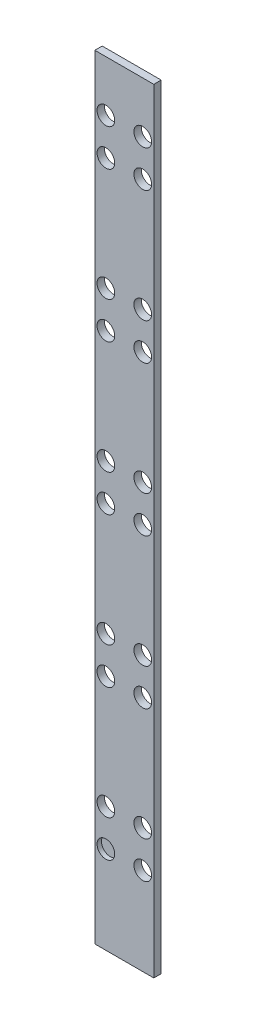
SolidWorks part; units mm, degrees
ref_plane "Front Plane" through (0, 0, 0) normal (0, 0, 1) x (1, 0, 0)
ref_plane "Top Plane" through (0, 0, 0) normal (0, 1, 0) x (1, 0, 0)
ref_plane "Right Plane" through (0, 0, 0) normal (1, 0, 0) x (0, 0, -1)
sketch "Sketch3" plane through (0, 0, 0) normal (0, 1, 0) x (1, 0, 0)
  line L0 (-2, 0.35) -> (-2, -0.15)
  line L1 (-2, -0.15) -> (2, -0.15)
  line L2 (2, -0.15) -> (2, 0.35)
  line L3 (2, 0.35) -> (-2, 0.35)
extrude "Boss-Extrude1" add sketch "Sketch3" against normal blind 52.5
sketch "Sketch4" plane through (0, 0, 0.15) normal (0, 0, 1) x (1, 0, 0)
  circle A0 centre (1.25, -3.45) radius 0.6
extrude "Cut-Extrude1" cut sketch "Sketch4" against normal blind 0.5
sketch "Sketch5" plane through (0, 0, 0.15) normal (0, 0, 1) x (1, 0, 0)
  circle A0 centre (1.25, -5.95) radius 0.6
  circle A2 centre (1.25, -3.45) radius 0.6 construction
  dimension "D1" = 2.5
extrude "Cut-Extrude2" cut sketch "Sketch5" against normal blind 0.5
sketch "Sketch6" plane through (0, 0, 0.15) normal (0, 0, 1) x (1, 0, 0)
  circle A0 centre (1.25, -13.6) radius 0.6
extrude "Cut-Extrude3" cut sketch "Sketch6" against normal blind 0.5
sketch "Sketch7" plane through (0, 0, 0.15) normal (0, 0, 1) x (1, 0, 0)
  circle A0 centre (1.25, -16.1) radius 0.6
extrude "Cut-Extrude4" cut sketch "Sketch7" against normal blind 0.5
sketch "Sketch8" plane through (0, 0, 0.15) normal (0, 0, 1) x (1, 0, 0)
  circle A0 centre (1.25, -23.75) radius 0.6
extrude "Cut-Extrude5" cut sketch "Sketch8" against normal blind 0.5
sketch "Sketch9" plane through (0, 0, 0.15) normal (0, 0, 1) x (1, 0, 0)
  circle A0 centre (1.25, -26.25) radius 0.6
extrude "Cut-Extrude6" cut sketch "Sketch9" against normal blind 0.5
sketch "Sketch10" plane through (0, 0, 0.15) normal (0, 0, 1) x (1, 0, 0)
  circle A0 centre (1.25, -33.9) radius 0.6
extrude "Cut-Extrude7" cut sketch "Sketch10" against normal blind 0.5
sketch "Sketch11" plane through (0, 0, 0.15) normal (0, 0, 1) x (1, 0, 0)
  circle A0 centre (1.25, -36.4) radius 0.6
extrude "Cut-Extrude8" cut sketch "Sketch11" against normal blind 0.5
sketch "Sketch12" plane through (0, 0, 0.15) normal (0, 0, 1) x (1, 0, 0)
  circle A0 centre (1.25, -44.05) radius 0.6
extrude "Cut-Extrude9" cut sketch "Sketch12" against normal blind 0.5
sketch "Sketch13" plane through (0, 0, 0.15) normal (0, 0, 1) x (1, 0, 0)
  circle A0 centre (1.25, -46.55) radius 0.6
extrude "Cut-Extrude10" cut sketch "Sketch13" against normal blind 0.5
sketch "Sketch14" plane through (0, 0, 0.15) normal (0, 0, 1) x (1, 0, 0)
  circle A0 centre (-1.25, -3.45) radius 0.6
extrude "Cut-Extrude11" cut sketch "Sketch14" against normal blind 0.5
sketch "Sketch15" plane through (0, 0, 0.15) normal (0, 0, 1) x (1, 0, 0)
  circle A0 centre (-1.25, -5.95) radius 0.6
extrude "Cut-Extrude12" cut sketch "Sketch15" against normal blind 0.5
sketch "Sketch16" plane through (0, 0, 0.15) normal (0, 0, 1) x (1, 0, 0)
  circle A0 centre (-1.25, -13.6) radius 0.6
extrude "Cut-Extrude13" cut sketch "Sketch16" against normal blind 0.5
sketch "Sketch17" plane through (0, 0, 0.15) normal (0, 0, 1) x (1, 0, 0)
  circle A0 centre (-1.25, -16.1) radius 0.6
extrude "Cut-Extrude14" cut sketch "Sketch17" against normal blind 0.5
sketch "Sketch18" plane through (0, 0, 0.15) normal (0, 0, 1) x (1, 0, 0)
  circle A0 centre (-1.25, -23.75) radius 0.6
extrude "Cut-Extrude15" cut sketch "Sketch18" against normal blind 0.5
sketch "Sketch19" plane through (0, 0, 0.15) normal (0, 0, 1) x (1, 0, 0)
  circle A0 centre (-1.25, -26.25) radius 0.6
extrude "Cut-Extrude16" cut sketch "Sketch19" against normal blind 0.5
sketch "Sketch20" plane through (0, 0, 0.15) normal (0, 0, 1) x (1, 0, 0)
  circle A0 centre (-1.25, -33.9) radius 0.6
extrude "Cut-Extrude17" cut sketch "Sketch20" against normal blind 0.5
sketch "Sketch21" plane through (0, 0, 0.15) normal (0, 0, 1) x (1, 0, 0)
  circle A0 centre (-1.25, -36.4) radius 0.6
extrude "Cut-Extrude18" cut sketch "Sketch21" against normal blind 0.5
sketch "Sketch22" plane through (0, 0, 0.15) normal (0, 0, 1) x (1, 0, 0)
  circle A0 centre (-1.25, -44.05) radius 0.6
extrude "Cut-Extrude19" cut sketch "Sketch22" against normal blind 0.5
sketch "Sketch23" plane through (0, 0, 0.15) normal (0, 0, 1) x (1, 0, 0)
  circle A0 centre (-1.25, -46.55) radius 0.6
extrude "Cut-Extrude20" cut sketch "Sketch23" against normal blind 0.3
